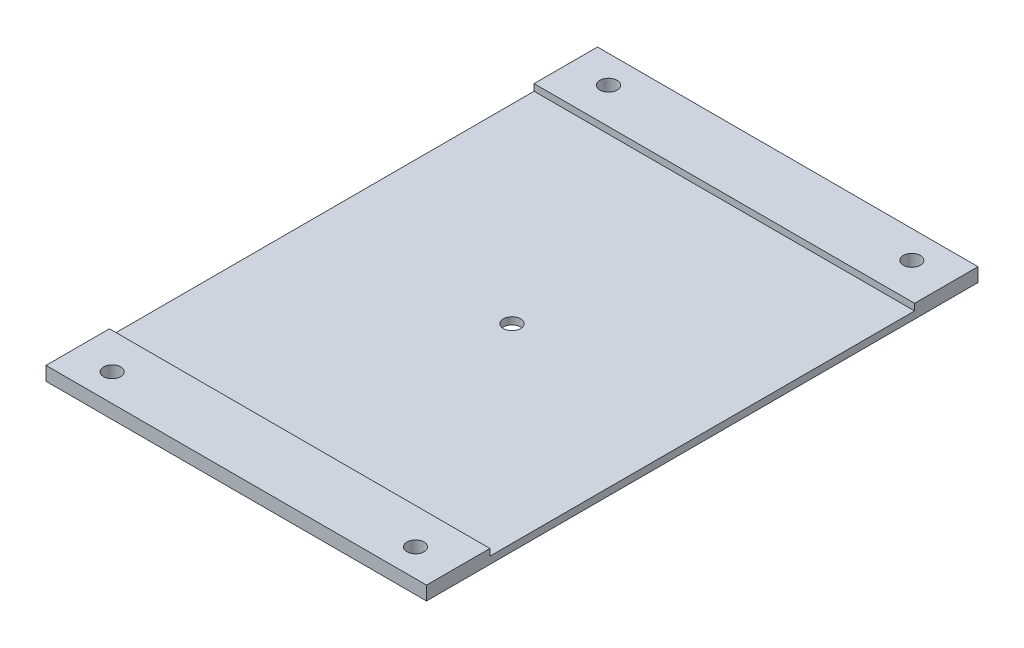
SolidWorks part; units mm, degrees
ref_plane "Front" through (0, 0, 0) normal (0, 0, 1) x (1, 0, 0)
ref_plane "Top" through (0, 0, 0) normal (0, 1, 0) x (1, 0, 0)
ref_plane "Right" through (0, 0, 0) normal (1, 0, 0) x (0, 0, -1)
sketch "Sketch1" plane through (0, 0, 0) normal (0, 1, 0) x (1, 0, 0)
  line L1 (-34.5, 50) -> (34.5, 50)
  line L2 (-34.5, 50) -> (-34.5, -50)
  line L3 (-34.5, -50) -> (34.5, -50)
  line L4 (34.5, 50) -> (34.5, -50)
  line L5 (-34.5, 50) -> (34.5, -50) construction
  line L6 (-34.5, -50) -> (34.5, 50) construction
  point P0 (0, 0)
  dimension "D1" = 100
  dimension "D2" = 69
extrude "Boss-Extrude1" add sketch "Sketch1" along normal blind 2.5
sketch "Sketch2" plane through (0, 2.5, 0) normal (0, 1, 0) x (1, 0, 0)
  line L1 (34.5, 38.5) -> (-34.5, 38.5)
  line L2 (34.5, 38.5) -> (34.5, -38.5)
  line L3 (34.5, -38.5) -> (-34.5, -38.5)
  line L4 (-34.5, 38.5) -> (-34.5, -38.5)
  line L5 (34.5, 38.5) -> (-34.5, -38.5) construction
  line L6 (34.5, -38.5) -> (-34.5, 38.5) construction
  point P1 (0, 0)
  dimension "D1" = 77
  dimension "D2" = 69
extrude "Cut-Extrude1" cut sketch "Sketch2" against normal blind 1.2
hole_wizard "M2.5 Clearance Hole1" positions "Sketch3" profile "Sketch4" hole size "M2.5" standard "ANSI Metric" end condition through all
sketch "Sketch3" plane through (0, 2.5, 0) normal (0, 1, 0) x (1, 0, 0)
  line L1 (27.5, 45) -> (-27.5, 45) construction
  line L2 (27.5, 45) -> (27.5, -45) construction
  line L3 (27.5, -45) -> (-27.5, -45) construction
  line L4 (-27.5, 45) -> (-27.5, -45) construction
  line L5 (27.5, 45) -> (-27.5, -45) construction
  line L6 (27.5, -45) -> (-27.5, 45) construction
  point P0 (-27.5, 45)
  point P2 (27.5, 45)
  point P4 (-27.5, -45)
  point P6 (27.5, -45)
  point P9 (0, 0)
  dimension "D1" = 90
  dimension "D2" = 55
sketch "Sketch4" plane through (-27.5, 2.5, -45) normal (1, 0, 0) x (0, 0, 1)
  line L0 (0, 0) -> (0, 2.5)
  line L1 (0, 2.5) -> (1.55, 2.5)
  line L2 (1.55, 2.5) -> (1.55, 0)
  line L5 (1.55, 0) -> (0, 0)
  line L11 (0, -6.35) -> (0, 107.95) construction
  dimension "Thru Hole Dia." = 3.1
  dimension "Thru Hole Depth" = 2.5
